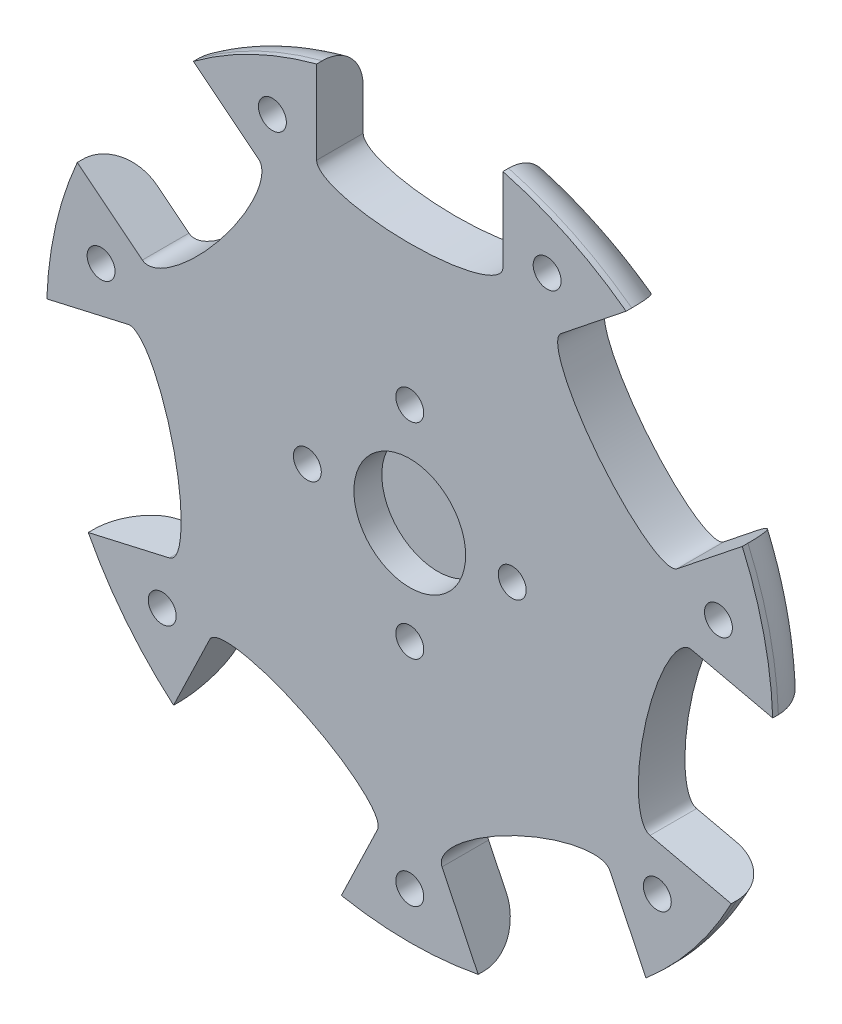
SolidWorks part; units mm, degrees
ref_plane "Front" through (0, 0, 0) normal (0, 0, 1) x (1, 0, 0)
ref_plane "Top" through (0, 0, 0) normal (0, 1, 0) x (1, 0, 0)
ref_plane "Right" through (0, 0, 0) normal (1, 0, 0) x (0, 0, -1)
sketch "草图1" plane through (0, 0, 0) normal (0, 0, 1) x (1, 0, 0)
  line L0 (0, -14.6841) -> (0, 53.021) construction
  line L1 (-15.8033, 33.5) -> (15.016, 33.5) construction
  line L2 (-10, 41) -> (10, 41) construction
  line L5 (-10, 31.5) -> (10, 31.5) construction
  line L6 (-10, 31.5) -> (-10, 26) construction
  line L7 (-10, 26) -> (10, 26) construction
  line L8 (10, 31.5) -> (10, 26) construction
  line L9 (-10, 28.75) -> (-10, 37.6962)
  line L10 (10, 28.75) -> (10, 37.6962)
  line L11 (16.2428, 25.7436) -> (23.2371, 31.3215)
  line L12 (28.7126, 10.107) -> (35.7069, 15.6849)
  line L13 (30.2544, 3.3518) -> (38.9762, 1.3611)
  line L14 (25.804, -16.1468) -> (34.5258, -18.1375)
  line L15 (21.4838, -21.564) -> (25.3654, -29.6242)
  line L16 (3.4645, -30.2417) -> (7.3461, -38.3019)
  line L17 (-3.4645, -30.2417) -> (-7.3461, -38.3019)
  line L18 (-21.4838, -21.564) -> (-25.3654, -29.6242)
  line L19 (-25.804, -16.1468) -> (-34.5258, -18.1375)
  line L20 (-30.2544, 3.3518) -> (-38.9762, 1.3611)
  line L21 (-28.7126, 10.107) -> (-35.7069, 15.6849)
  line L22 (-16.2428, 25.7436) -> (-23.2371, 31.3215)
  arc A0 (-10, 37.6962) -> (-23.2371, 31.3215) centre (0, 0) ccw
  arc A1 (-35.7069, 15.6849) -> (-38.9762, 1.3611) centre (0, 0) ccw
  arc A2 (-34.5258, -18.1375) -> (-25.3654, -29.6242) centre (0, 0) ccw
  arc A3 (-7.3461, -38.3019) -> (7.3461, -38.3019) centre (0, 0) ccw
  arc A4 (25.3654, -29.6242) -> (34.5258, -18.1375) centre (0, 0) ccw
  arc A5 (38.9762, 1.3611) -> (35.7069, 15.6849) centre (0, 0) ccw
  arc A6 (23.2371, 31.3215) -> (10, 37.6962) centre (0, 0) ccw
  ellipse E0 centre (0, 28.75) end of major axis (10, 28.75) minor radius 2.75 (-10, 28.75) -> (10, 28.75) ccw
  ellipse E1 centre (22.4777, 17.9253) end of major axis (28.7126, 10.107) minor radius 2.75 (16.2428, 25.7436) -> (28.7126, 10.107) ccw
  ellipse E2 centre (28.0292, -6.3975) end of major axis (25.804, -16.1468) minor radius 2.75 (30.2544, 3.3518) -> (25.804, -16.1468) ccw
  ellipse E3 centre (12.4742, -25.9029) end of major axis (3.4645, -30.2417) minor radius 2.75 (21.4838, -21.564) -> (3.4645, -30.2417) ccw
  ellipse E4 centre (-12.4742, -25.9029) end of major axis (-21.4838, -21.564) minor radius 2.75 (-3.4645, -30.2417) -> (-21.4838, -21.564) ccw
  ellipse E5 centre (-28.0292, -6.3975) end of major axis (-30.2544, 3.3518) minor radius 2.75 (-25.804, -16.1468) -> (-30.2544, 3.3518) ccw
  ellipse E6 centre (-22.4777, 17.9253) end of major axis (-16.2428, 25.7436) minor radius 2.75 (-28.7126, 10.107) -> (-16.2428, 25.7436) ccw
  point P79 (0, 0)
  dimension "D1" = 78
  dimension "D2" = 20
  dimension "D3" = 10
  dimension "D4" = 2
  dimension "D5" = 7.5
  dimension "D6" = 41
  dimension "D7" = 7
extrude "凸台-拉伸2" add sketch "草图1" along normal blind 5
sketch "草图3" plane through (0, 0, 5) normal (0, 0, 1) x (1, 0, 0)
  line L0 (0, 0) -> (16.9215, 35.1378) construction
  circle A0 centre (0, 0) radius 11 construction
  circle A1 centre (0, 11) radius 1.5
  circle A2 centre (11, 0) radius 1.5
  circle A3 centre (0, -11) radius 1.5
  circle A4 centre (-11, 0) radius 1.5
  circle A5 centre (0, 0) radius 6
  circle A6 centre (0, 0) radius 34 construction
  circle A7 centre (14.752, 30.6329) radius 1.5
  arc A8 (23.2371, 31.3215) -> (10, 37.6962) centre (0, 0) ccw construction
  circle A9 centre (33.1475, 7.5657) radius 1.5
  circle A10 centre (26.5823, -21.1987) radius 1.5
  circle A11 centre (0, -34) radius 1.5
  circle A12 centre (-26.5823, -21.1987) radius 1.5
  circle A13 centre (-33.1475, 7.5657) radius 1.5
  circle A14 centre (-14.752, 30.6329) radius 1.5
  point P14 (0, 0)
  point P35 (0, 0)
  dimension "D1" = 4
  dimension "D2" = 3
  dimension "D3" = 68
  dimension "D4" = 7
extrude "切除-拉伸2" cut sketch "草图3" against normal blind 3
scale "缩放比例1" scale about centroid uniform scaling yes scale factor 0.683
fillet "圆角2" radius 3 7 edges at (-11.5574, 23.9991, 0.7803) (-25.9692, 5.9273, 0.7803) (-20.8256, -16.6079, 0.7803) (0, -26.637, 0.7803) (20.8256, -16.6079, 0.7803) (25.9692, 5.9273, 0.7803) (11.5574, 23.9991, 0.7803)
